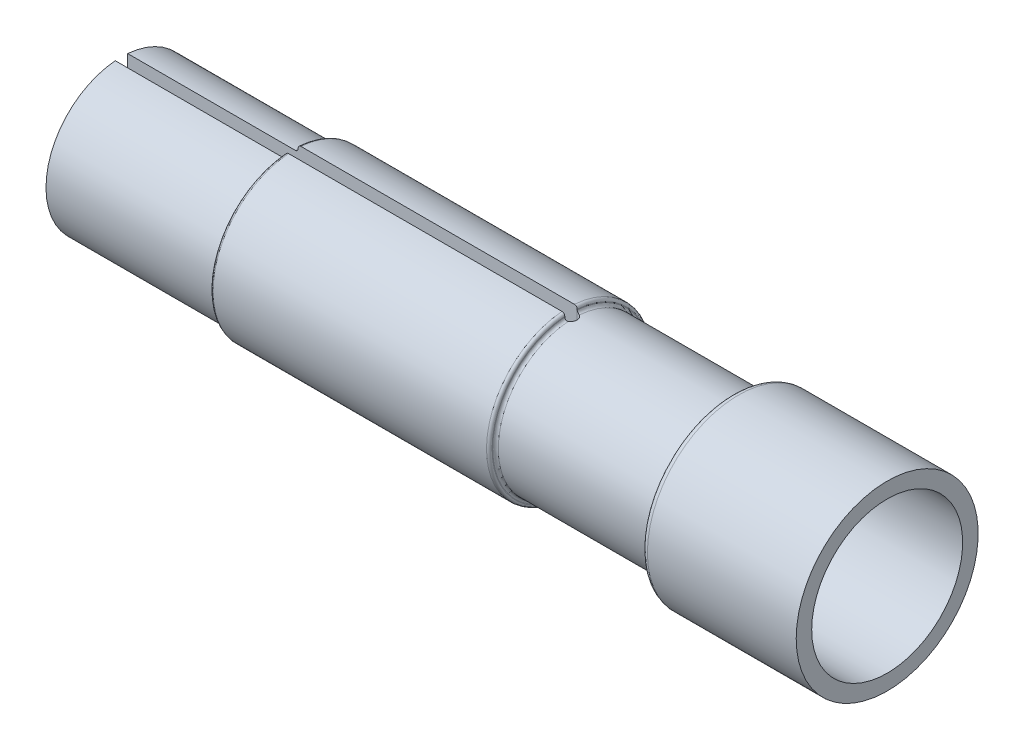
SolidWorks part; units mm, degrees
material "PVC 0.007 Plasticized"
ref_plane "Front" through (0, 0, 0) normal (0, 0, 1) x (1, 0, 0)
ref_plane "Top" through (0, 0, 0) normal (0, 1, 0) x (1, 0, 0)
ref_plane "Right" through (0, 0, 0) normal (1, 0, 0) x (0, 0, -1)
sketch "Sketch1" plane through (0, 0, 0) normal (0, 1, 0) x (1, 0, 0)
  line L0 (-16.2, 0) -> (16.2, 0) construction
  line L1 (-16.2, 8.655) -> (16.2, 8.655) construction
  line L2 (-16.2, 8.655) -> (-16.2, -8.655) construction
  line L3 (-16.2, -8.655) -> (16.2, -8.655) construction
  line L4 (16.2, 8.655) -> (16.2, -8.655) construction
  line L5 (-4, 0) -> (-4, 2.135) construction
  line L6 (-4, 2.135) -> (4, 2.135) construction
  line L7 (4, 2.135) -> (4, 0) construction
  line L8 (-10, 0) -> (-10, 1.935) construction
  line L9 (-10, 1.935) -> (-4, 1.935) construction
  line L10 (4, 1.935) -> (14.7, 1.935) construction
  line L11 (14.7, 1.935) -> (14.7, 0) construction
  line L12 (16.2, 2.435) -> (10.2, 2.435) construction
  line L13 (10.2, 2.435) -> (10.2, 0) construction
  line L14 (14.7, 2.435) -> (10.2, 2.435)
  line L15 (10.2, 2.435) -> (10.2, 1.935)
  line L16 (10.2, 1.935) -> (4, 1.935)
  line L17 (4, 1.935) -> (4, 2.135)
  line L18 (4, 2.135) -> (-4, 2.135)
  line L19 (-4, 2.135) -> (-4, 1.935)
  line L20 (-4, 1.935) -> (-10, 1.935)
  line L21 (14.7, 2.935) -> (9.9, 2.935)
  line L22 (9.7, 2.735) -> (9.7, 2.635)
  line L23 (9.5, 2.435) -> (4.59, 2.435)
  line L24 (4.5, 2.525) -> (4.5, 2.545)
  line L25 (4.41, 2.635) -> (-4.41, 2.635)
  line L26 (-4.5, 2.545) -> (-4.5, 2.525)
  line L27 (-4.59, 2.435) -> (-10, 2.435)
  line L28 (-10, 1.935) -> (-10, 2.435)
  line L29 (14.7, 2.935) -> (14.7, 2.435)
  line L30 (-4.5, 2.635) -> (-4.5, 2.435) construction
  line L31 (-4.5, 2.435) -> (-10, 2.435) construction
  line L32 (4.5, 2.635) -> (-4.5, 2.635) construction
  line L33 (9.7, 2.435) -> (4.5, 2.435) construction
  line L34 (4.5, 2.435) -> (4.5, 2.635) construction
  line L35 (9.7, 2.935) -> (9.7, 2.435) construction
  line L36 (14.7, 2.935) -> (9.7, 2.935) construction
  arc A0 (-4.5, 2.525) -> (-4.59, 2.435) centre (-4.59, 2.525) cw
  arc A1 (-4.41, 2.635) -> (-4.5, 2.545) centre (-4.41, 2.545) ccw
  arc A2 (4.59, 2.435) -> (4.5, 2.525) centre (4.59, 2.525) cw
  arc A3 (4.5, 2.545) -> (4.41, 2.635) centre (4.41, 2.545) ccw
  arc A4 (9.7, 2.635) -> (9.5, 2.435) centre (9.5, 2.635) cw
  arc A5 (9.9, 2.935) -> (9.7, 2.735) centre (9.9, 2.735) ccw
  point P5 (0, 2.135)
  dimension "D10" = 0.09
  dimension "D11" = 0.2
  dimension "D1" = 32.4
  dimension "D2" = 8
  dimension "D3" = 1.935
  dimension "D4" = 2.135
  dimension "D5" = 1.5
  dimension "D6" = 6
  dimension "D7" = 6
  dimension "D8" = 0.5
  dimension "D9" = 0.5
revolve "Revolve1" add sketch "Sketch1" angle 360 about L0
sketch "Sketch3" plane through (0, 0, 0) normal (0, 1, 0) x (1, 0, 0)
  line L0 (-10, 2.435) -> (-10, -2.435) construction
  line L1 (4.5, -2.525) -> (4.5, 2.525) construction
  line L2 (-10, 0.2) -> (4.5, 0.2)
  line L3 (-10, 0.2) -> (-10, -0.2)
  line L4 (-10, -0.2) -> (4.5, -0.2)
  line L5 (4.5, 0.2) -> (4.5, -0.2) construction
  line L6 (-10, 0.2) -> (4.5, -0.2) construction
  line L7 (-10, -0.2) -> (4.5, 0.2) construction
  arc A0 (4.5, -0.2) -> (4.5, 0.2) centre (4.5, 0) ccw
  point P6 (-2.75, 0)
  point P7 (4.489, -0.2)
  point P12 (0, 0)
  dimension "D1" = 0.4
extrude "Cut-Extrude2" cut sketch "Sketch3" along normal through all contours L2 A0 L4 L3
equation "\"D7@Sketch1\"=\"D6@Sketch1\""
